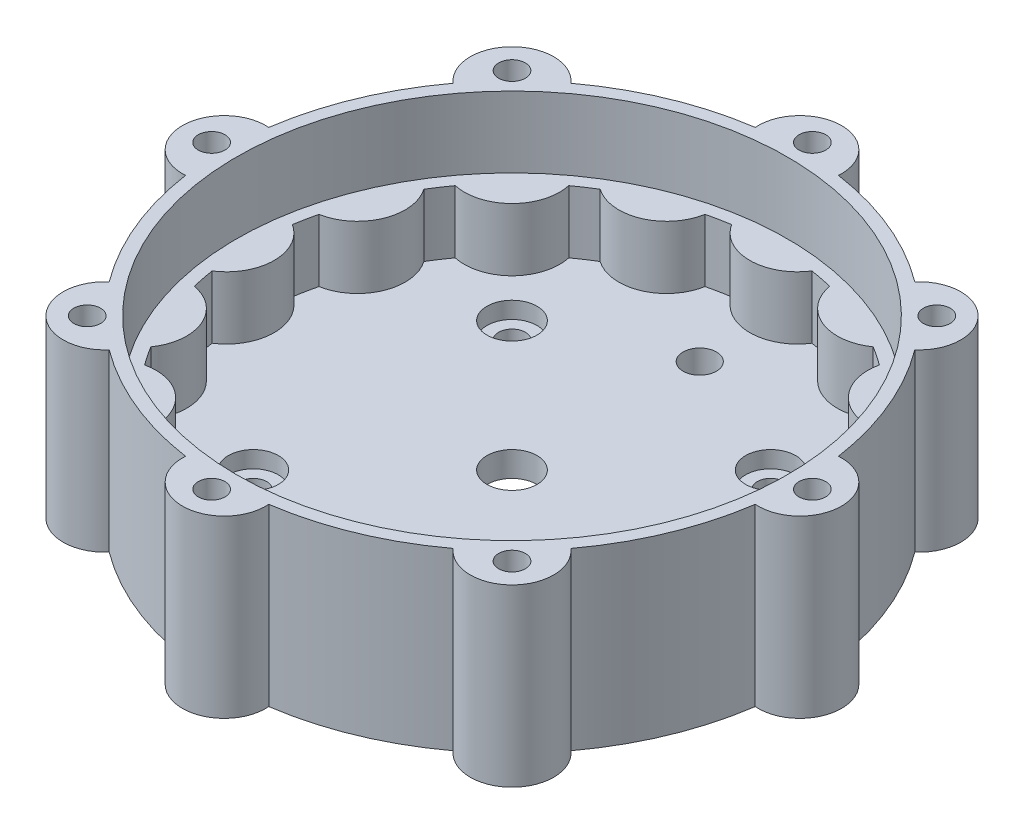
SolidWorks part; units mm, degrees
ref_plane "Front Plane" through (0, 0, 0) normal (0, 0, 1) x (1, 0, 0)
ref_plane "Top Plane" through (0, 0, 0) normal (0, 1, 0) x (1, 0, 0)
ref_plane "Right Plane" through (0, 0, 0) normal (1, 0, 0) x (0, 0, -1)
sketch "Sketch1" plane through (0, 0, 0) normal (0, 1, 0) x (1, 0, 0)
  circle A2 centre (0, 0) radius 34.5
  dimension "D1" = 69
extrude "Boss-Extrude1" add sketch "Sketch1" against normal blind 5
sketch "Sketch4" plane through (0, 0, 0) normal (0, 1, 0) x (1, 0, 0)
  circle A0 centre (0, 0) radius 34.5
  circle A1 centre (0, 0) radius 31.5
  circle A2 centre (0, 0) radius 34.5 construction
  dimension "D1" = 3
extrude "Boss-Extrude2" add sketch "Sketch4" along normal blind 7.5
sketch "Sketch5" plane through (0, 0, 0) normal (0, 1, 0) x (1, 0, 0)
  circle A0 centre (0, 0) radius 3
  dimension "D1" = 6
extrude "Cut-Extrude1" cut sketch "Sketch5" against normal through all
sketch "Sketch6" plane through (0, 0, 0) normal (0, 1, 0) x (1, 0, 0)
  circle A0 centre (-15.5, 15.5) radius 3
  circle A1 centre (15.5, 15.5) radius 3
  circle A2 centre (15.5, -15.5) radius 3
  circle A3 centre (-15.5, -15.5) radius 3
  dimension "D1" = 6
  dimension "D4" = 15.5
  dimension "D5" = 15.5
  dimension "D6" = 15.5
  dimension "D7" = 15.5
  dimension "D2" = 2
  dimension "D3" = 2
extrude "Cut-Extrude2" cut sketch "Sketch6" against normal blind 2
sketch "Sketch8" plane through (0, 0, 0) normal (0, 1, 0) x (1, 0, 0)
  circle A0 centre (-15.5, 15.5) radius 1.6
  circle A1 centre (15.5, 15.5) radius 1.6
  circle A2 centre (15.5, -15.5) radius 1.6
  circle A3 centre (-15.5, -15.5) radius 1.6
  dimension "D1" = 3.2
  dimension "D4" = 31
  dimension "D5" = 31
  dimension "D2" = 2
  dimension "D3" = 2
extrude "Cut-Extrude3" cut sketch "Sketch8" against normal through all
sketch "Sketch9" plane through (0, 0, 0) normal (0, 1, 0) x (1, 0, 0)
  line L1 (-2.5416, 34.4062) -> (2.5416, 34.4062)
  arc A0 (-2.5416, 34.4062) -> (2.5416, 34.4062) centre (0, 32) ccw
  circle A3 centre (0, 0) radius 34.5 construction
  arc A4 (-4.8109, 31.1305) -> (4.8109, 31.1305) centre (0, 34.2146) ccw
  circle A5 centre (0, 0) radius 31.5 construction
  circle A6 centre (0, 0) radius 31.5 construction
  circle M6 centre (0, 0) radius 31.5
  dimension "D1" = 7
  dimension "D2" = 32
extrude "Boss-Extrude3" add sketch "Sketch9" along normal blind 7.5 contours A4 A0 M6 | A0 A4 M6
pattern_circular "CirPattern1" count 16 over 360 about axis through (0, 0, 0) along (0, 1, 0) of "Boss-Extrude3"
sketch "Sketch10" plane through (0, -5, 0) normal (0, -1, 0) x (-1, 0, 0)
  circle A0 centre (0, 0) radius 11.5
  dimension "D1" = 23
extrude "Cut-Extrude4" cut sketch "Sketch10" against normal blind 2
sketch "Sketch11" plane through (0, 7.5, 0) normal (0, 1, 0) x (1, 0, 0)
  circle A0 centre (0, 0) radius 34.5
  circle A1 centre (0, 0) radius 33
  dimension "D1" = 66
  dimension "D2" = 69
extrude "Boss-Extrude4" add sketch "Sketch11" along normal blind 8.5
sketch "Sketch12" plane through (0, -5, 0) normal (0, -1, 0) x (1, 0, 0)
  arc A0 (4.9869, 34.1377) -> (-4.9869, 34.1377) centre (0, 34.5) ccw
  circle A1 centre (0, 0) radius 34.5 construction
  circle A4 centre (0, 0) radius 34.5
  circle A5 centre (0, 0) radius 34.5
  circle M8 centre (0, 0) radius 34.5
  dimension "D1" = 10
  dimension "D2" = 0
extrude "Boss-Extrude5" add sketch "Sketch12" against normal up to surface (21 mm away) contours A0 M8 up to face at (0, 16, 34.5)
sketch "Sketch15" plane through (0, 16, 0) normal (0, 1, 0) x (1, 0, 0)
  circle A0 centre (0, -36) radius 1.6
  dimension "D1" = 3.2
  dimension "D2" = 36
extrude "Cut-Extrude5" cut sketch "Sketch15" against normal blind 15
pattern_circular "CirPattern2" count 8 over 360 about axis through (0, 0, 0) along (0, 1, 0) of "Boss-Extrude5", "Cut-Extrude5"
sketch "Sketch16" plane through (0, 0, 0) normal (0, 1, 0) x (1, 0, 0)
  circle A0 centre (0, 22.5) radius 2
  dimension "D1" = 4
  dimension "D2" = 22.5
extrude "Cut-Extrude6" cut sketch "Sketch16" against normal through all
